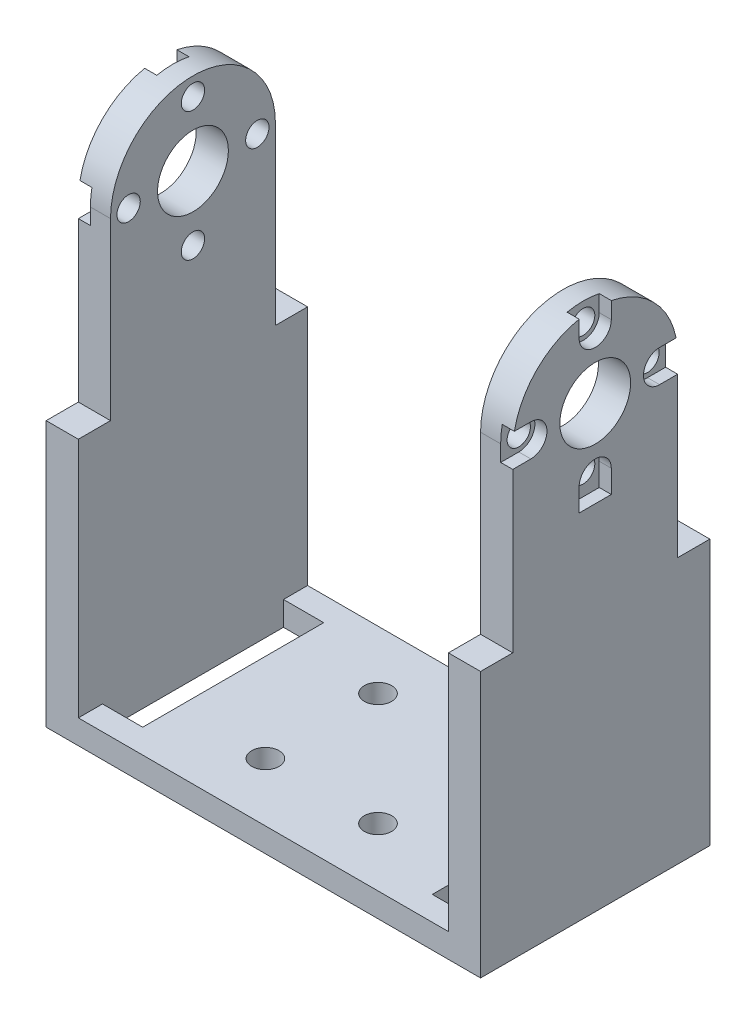
SolidWorks part; units mm, degrees
ref_plane "Front Plane" through (0, 0, 0) normal (0, 0, 1) x (1, 0, 0)
ref_plane "Top Plane" through (0, 0, 0) normal (0, 1, 0) x (1, 0, 0)
ref_plane "Right Plane" through (0, 0, 0) normal (1, 0, 0) x (0, 0, -1)
sketch "Sketch1" plane through (0, 0, 0) normal (0, 1, 0) x (1, 0, 0)
  line L0 (0, 0) -> (0, -7.6155) construction
  line L1 (-18, 14.25) -> (18, 14.25)
  line L2 (-18, 14.25) -> (-18, -14.25)
  line L3 (-18, -14.25) -> (18, -14.25)
  line L4 (18, 14.25) -> (18, -14.25)
  line L5 (0, 0) -> (0, 12.9892) construction
  line L6 (-18, 14.25) -> (-27, 14.25)
  line L7 (-18, 14.25) -> (-18, -14.25)
  line L8 (-18, -14.25) -> (-27, -14.25)
  line L9 (-27, 14.25) -> (-27, -14.25)
  line L10 (18, 14.25) -> (27, 14.25)
  line L11 (18, 14.25) -> (18, -14.25)
  line L12 (18, -14.25) -> (27, -14.25)
  line L13 (27, 14.25) -> (27, -14.25)
  line L14 (-23, 11.25) -> (-18, 11.25)
  line L15 (-23, 11.25) -> (-23, -11.25)
  line L16 (-23, -11.25) -> (-18, -11.25)
  line L17 (-18, 11.25) -> (-18, -11.25)
  line L18 (18, 11.25) -> (18, -11.25)
  line L19 (23, -11.25) -> (18, -11.25)
  line L20 (23, 11.25) -> (23, -11.25)
  line L21 (23, 11.25) -> (18, 11.25)
  circle A0 centre (0, 0) radius 7.5
  circle A1 centre (-9, 8.25) radius 1.7
  circle A2 centre (-9, -8.25) radius 1.7
  circle A3 centre (9, -8.25) radius 1.7
  circle A4 centre (9, 8.25) radius 1.7
  point P0 (0, 0)
  dimension "D3" = 9
  dimension "D4" = 8.25
  dimension "D5" = 8.25
  dimension "D6" = 9
  dimension "D7" = 9
  dimension "D9" = 15
  dimension "D14" = 3.4
  dimension "D1" = 36
  dimension "D2" = 28.5
  dimension "D8" = 9
  dimension "D10" = 4
  dimension "D11" = 3
  dimension "D12" = 3
  dimension "D13" = 5
extrude "Boss-Extrude2" add sketch "Sketch1" along normal blind 3
sketch "Sketch2" plane through (0, 3, 0) normal (0, 1, 0) x (1, 0, 0)
  line L5 (27, 14.25) -> (27, -14.25) construction
  line L6 (27, 10.25) -> (23, 10.25)
  line L7 (27, 10.25) -> (27, -10.25)
  line L8 (27, -10.25) -> (23, -10.25)
  line L9 (23, 10.25) -> (23, -10.25)
  line L10 (27, 14.25) -> (-27, 14.25) construction
  dimension "D1" = 4
  dimension "D2" = 20.5
  dimension "D3" = 4
extrude "Boss-Extrude3" add sketch "Sketch2" along normal blind 21.75
sketch "Sketch4" plane through (27, 0, 0) normal (1, 0, 0) x (0, 0, -1)
  line L0 (-10.25, 24.75) -> (10.25, 24.75) construction
  circle A0 centre (0, 24.75) radius 10.25
  point P18 (0, 17.75)
extrude "Boss-Extrude4" add sketch "Sketch4" against normal blind 4
ref_plane "Plane1" through (0, 0, 0) normal (1, 0, 0) x (0, 0, -1)
mirror "Mirror1" about plane through (0, 0, 0) normal (1, 0, 0) of "Boss-Extrude3", "Boss-Extrude4"
sketch "Sketch6" plane through (27, 0, 0) normal (1, 0, 0) x (0, 0, -1)
  line L0 (-10.25, 24.75) -> (10.25, 24.75) construction
  line L1 (0, 35) -> (0, 14.5) construction
  circle A6 centre (0, 24.75) radius 4.4
  circle A7 centre (0, 24.75) radius 8
  circle A8 centre (0, 32.75) radius 1.45
  circle A9 centre (8, 24.75) radius 1.45
  circle A10 centre (0, 16.75) radius 1.45
  circle A11 centre (-8, 24.75) radius 1.45
  circle A12 centre (0, 24.75) radius 10.25
  point P21 (0, 24.75)
  dimension "D1" = 8.8
  dimension "D2" = 16
  dimension "D3" = 4
  dimension "D4" = 2.9
extrude "Cut-Extrude3" cut sketch "Sketch6" against normal blind 4 contours A6 | A7 A11 | A7 A11 | A7 A10 | A7 A10 | A7 A9 | A7 A9 | A7 A8 | A7 A8
mirror "Mirror3" about plane through (0, 0, 0) normal (1, 0, 0) of "Cut-Extrude3"
sketch "Sketch7" plane through (27, 0, 0) normal (1, 0, 0) x (0, 0, -1)
  line L0 (10.8224, 26.75) -> (10.8224, 22.75)
  line L2 (-2, 32.75) -> (-2, 35.5724)
  line L3 (-2, 35.5724) -> (2, 35.5724)
  line L4 (2, 32.75) -> (2, 35.5724)
  line L5 (8, 22.75) -> (10.8224, 22.75)
  line L6 (8, 26.75) -> (10.8224, 26.75)
  line L7 (2, 13.9276) -> (-2, 13.9276)
  line L8 (-2, 16.75) -> (-2, 13.9276)
  line L9 (2, 16.75) -> (2, 13.9276)
  line L10 (-10.8224, 22.75) -> (-10.8224, 26.75)
  line L11 (-8, 26.75) -> (-10.8224, 26.75)
  line L12 (-8, 22.75) -> (-10.8224, 22.75)
  circle A0 centre (0, 32.75) radius 2
  circle A1 centre (0, 24.75) radius 8
  circle A2 centre (8, 24.75) radius 2
  circle A3 centre (0, 16.75) radius 2
  circle A4 centre (-8, 24.75) radius 2
  point P15 (0, 24.75)
  point P32 (0, 24.75)
  circle M1 centre (-8, 24.75) radius 1.45
  circle M2 centre (0, 16.75) radius 1.45
  circle M3 centre (8, 24.75) radius 1.45
  circle M4 centre (0, 32.75) radius 1.45
  line M6 (10.25, 3) -> (10.25, 24.75)
  arc M7 (10.25, 24.75) -> (-10.25, 24.75) centre (0, 24.75) ccw
  line M8 (-10.25, 24.75) -> (-10.25, 3)
  dimension "D1" = 4
  dimension "D3" = 4
  dimension "D2" = 4
  dimension "D4" = 4
extrude "Cut-Extrude4" cut sketch "Sketch7" against normal blind 1.5 contours A1 M1 | A1 M1 | A1 A0 M4 | A0 A1 M4 | A1 A2 M3 | A1 A2 M3 | A1 A3 M2 | A1 A3 M2 | L4 L3 L2 M7 | A0 L4 L2 M7 | A2 L5 L6 M6 M7 | A3 L8 L7 L9 | A4 L11 L12 M7 M8
mirror "Mirror4" about plane through (0, 0, 0) normal (1, 0, 0) of "Cut-Extrude4"
sketch "Sketch8" plane through (0, 3, 0) normal (0, 1, 0) x (1, 0, 0)
  line L0 (27, -14.25) -> (-27, -14.25) construction
  line L1 (-14.3907, 14.25) -> (14.3907, 14.25)
  line L2 (-14.3907, 14.25) -> (-14.3907, -14.25)
  line L3 (-14.3907, -14.25) -> (14.3907, -14.25)
  line L4 (14.3907, 14.25) -> (14.3907, -14.25)
  line L5 (-14.3907, 14.25) -> (14.3907, -14.25) construction
  line L6 (-14.3907, -14.25) -> (14.3907, 14.25) construction
  point P0 (0, 0)
extrude "Boss-Extrude5" add sketch "Sketch8" against normal blind 3
sketch "Sketch9" plane through (0, 3, 0) normal (0, 1, 0) x (1, 0, 0)
  line L3 (-7, 7) -> (7, 7)
  line L4 (-7, 7) -> (-7, -7)
  line L5 (-7, -7) -> (7, -7)
  line L6 (7, 7) -> (7, -7)
  line L7 (-7, 7) -> (7, -7) construction
  line L8 (-7, -7) -> (7, 7) construction
  circle A0 centre (0, 0) radius 5
  circle A2 centre (-7, 7) radius 1.7
  circle A3 centre (7, 7) radius 1.7
  circle A4 centre (7, -7) radius 1.7
  circle A5 centre (-7, -7) radius 1.7
  dimension "D1" = 14
  dimension "D2" = 14
  dimension "D3" = 10
  dimension "D4" = 3.4
  dimension "D5" = 2
  dimension "D6" = 2
extrude "Cut-Extrude5" cut sketch "Sketch9" against normal blind 3 contours L4 A5 L5 | L5 A4 L6 | L6 A3 L3 | L3 A3 L6 | L5 A5 L4 | L6 A4 L5 | A2
sketch "Sketch10" plane through (0, 0, 0) normal (0, -1, 0) x (1, 0, 0)
  line L1 (-27, 14.25) -> (27, 14.25)
  line L2 (-27, 14.25) -> (-27, -14.25)
  line L3 (-27, -14.25) -> (27, -14.25)
  line L4 (27, 14.25) -> (27, -14.25)
  line L5 (-23, 11.25) -> (-18, 11.25)
  line L6 (-23, 11.25) -> (-23, -11.25)
  line L7 (-23, -11.25) -> (-18, -11.25)
  line L8 (-18, 11.25) -> (-18, -11.25)
  line L9 (18, -11.25) -> (23, -11.25)
  line L10 (18, -11.25) -> (18, 11.25)
  line L11 (18, 11.25) -> (23, 11.25)
  line L12 (23, -11.25) -> (23, 11.25)
  circle A0 centre (-7, 7) radius 1.7
  circle A1 centre (7, 7) radius 1.7
  circle A2 centre (7, -7) radius 1.7
  circle A3 centre (-7, -7) radius 1.7
extrude "Boss-Extrude7" add sketch "Sketch10" along normal blind 30
sketch "Sketch11" plane through (0, 0, 14.25) normal (0, 0, 1) x (1, 0, 0)
  line L0 (27, -30) -> (-27, -30) construction
  line L1 (-23, 3) -> (23, 3)
  line L2 (-23, 3) -> (-23, -27)
  line L3 (-23, -27) -> (23, -27)
  line L4 (23, 3) -> (23, -27)
  dimension "D1" = 3
extrude "Cut-Extrude6" cut sketch "Sketch11" against normal blind 30
